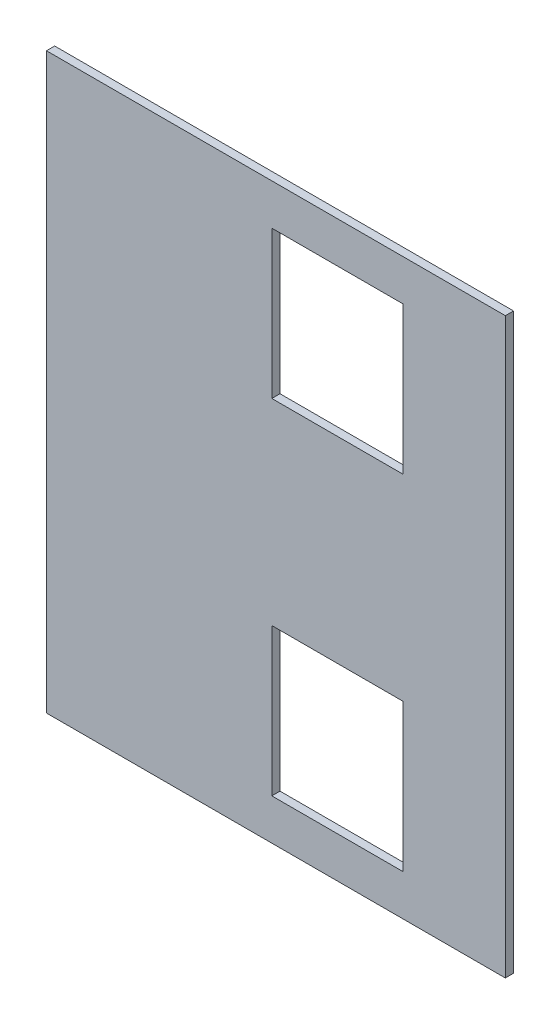
SolidWorks part; units mm, degrees
ref_plane "前视基准面" through (0, 0, 0) normal (0, 0, 1) x (1, 0, 0)
ref_plane "上视基准面" through (0, 0, 0) normal (0, 1, 0) x (1, 0, 0)
ref_plane "右视基准面" through (0, 0, 0) normal (1, 0, 0) x (0, 0, -1)
sketch "草图1" plane through (0, 0, 0) normal (0, 0, 1) x (1, 0, 0)
  line L1 (0, 0) -> (560, 0)
  line L2 (0, 0) -> (0, -700)
  line L3 (0, -700) -> (560, -700)
  line L4 (560, 0) -> (560, -700)
extrude "凸台-拉伸1" add sketch "草图1" along normal blind 10
sketch "草图2" plane through (0, 0, 10) normal (0, 0, 1) x (1, 0, 0)
  line L0 (560, -700) -> (560, 0) construction
  line L1 (275, -50) -> (435, -50)
  line L2 (275, -50) -> (275, -230)
  line L3 (275, -230) -> (435, -230)
  line L4 (435, -50) -> (435, -230)
  line L5 (560, 0) -> (0, 0) construction
  line L6 (-109.8474, -350) -> (765.6733, -350) construction
  line L7 (0, -700) -> (560, -700) construction
  line L8 (435, -650) -> (435, -470)
  line L9 (275, -470) -> (435, -470)
  line L10 (275, -650) -> (275, -470)
  line L11 (275, -650) -> (435, -650)
  dimension "D1" = 160
  dimension "D2" = 125
  dimension "D3" = 50
  dimension "D4" = 180
extrude "切除-拉伸1" cut sketch "草图2" against normal blind 10
